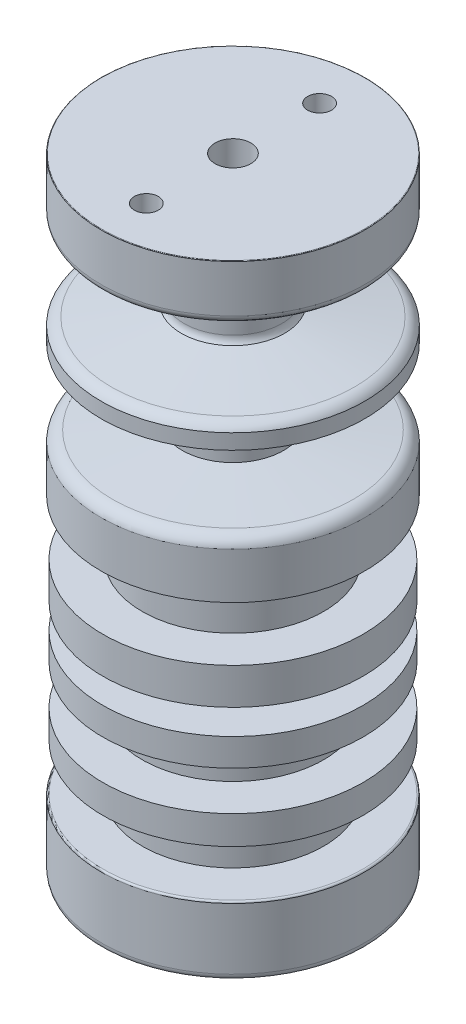
SolidWorks part; units mm, degrees
ref_plane "Alzado" through (0, 0, 0) normal (0, 0, 1) x (1, 0, 0)
ref_plane "Planta" through (0, 0, 0) normal (0, 1, 0) x (1, 0, 0)
ref_plane "Vista lateral" through (0, 0, 0) normal (1, 0, 0) x (0, 0, -1)
sketch "Croquis1" plane through (0, 0, 0) normal (0, 0, 1) x (1, 0, 0)
  line L0 (0, 0) -> (0, 43.0446) construction
  line L1 (0, 43.0446) -> (0, -121.9554) construction
  line L2 (0, 43.0446) -> (34.8584, 43.0446)
  line L3 (35, 42.903) -> (35, 30.366)
  line L4 (32.9644, 28.3304) -> (12.9858, 28.3304)
  line L5 (12.9858, 28.3304) -> (12.9858, 10.4062)
  line L6 (13.718, 8.5125) -> (32.3097, 5.486)
  line L7 (35, 3.5416) -> (35, -0.4901)
  line L8 (13.4687, -0.4901) -> (35, -0.4901)
  line L9 (13.4687, -0.4901) -> (13.4687, -18.5388)
  line L10 (13.4687, -18.5388) -> (31.9792, -20.5132)
  line L11 (35, -23.2242) -> (35, -35.5011)
  line L12 (24.0861, -91.9234) -> (34.5383, -91.9234)
  line L13 (24.0861, -91.9234) -> (24.0861, -104.2217)
  line L14 (24.0861, -104.2217) -> (34.5383, -104.2217)
  line L15 (35, -104.6833) -> (35, -120.9509)
  line L16 (34.7378, -121.991) -> (0, -121.9554)
  line L17 (0, 43.0446) -> (0, -121.9554)
  line L18 (34.5383, -91.9234) -> (34.5383, -84.3501)
  line L19 (35, -35.5011) -> (24.0861, -35.5011)
  line L20 (24.0861, -35.5011) -> (24.0861, -50.2633)
  line L21 (34.5383, -84.3501) -> (24.0861, -84.3501)
  line L22 (24.0861, -73.9073) -> (34.5383, -73.9073)
  line L23 (34.5383, -73.9073) -> (34.5383, -66.6171)
  line L24 (34.5383, -66.6171) -> (24.0861, -66.6171)
  line L25 (24.0861, -59.9179) -> (34.5383, -59.9179)
  line L26 (34.5383, -59.9179) -> (34.5383, -50.2633)
  line L27 (34.5383, -50.2633) -> (24.0861, -50.2633)
  line L28 (24.0861, -73.9073) -> (24.0861, -84.3501)
  line L29 (24.0861, -59.9179) -> (24.0861, -66.6171)
  arc A0 (34.8584, 43.0446) -> (35, 42.903) centre (34.8584, 42.903) cw
  arc A1 (35, 30.366) -> (32.9644, 28.3304) centre (32.9644, 30.366) cw
  arc A2 (12.9858, 10.4062) -> (13.718, 8.5125) centre (15.8008, 10.4062) ccw
  arc A3 (32.3097, 5.486) -> (35, 3.5416) centre (31.7144, 1.829) cw
  arc A6 (31.9792, -20.5132) -> (35, -23.2242) centre (31.6114, -23.9615) cw
  arc A8 (34.5383, -104.2217) -> (35, -104.6833) centre (34.5383, -104.6833) cw
  arc A9 (35, -120.9509) -> (34.7378, -121.991) centre (32.8058, -120.9509) cw
  dimension "D1" = 165
  dimension "D2" = 34.8584
  dimension "D3" = 35
  dimension "D4" = 35
  dimension "D5" = 35
revolve "Revolución3" add sketch "Croquis1" angle 360 about L17
sketch "Croquis2" plane through (0, 43.0446, 0) normal (0, 1, 0) x (1, 0, 0)
  line L1 (-0.2111, -19.8252) -> (0, 0) construction
  line L2 (0, 0) -> (11.2888, 0) construction
  line L4 (34.8584, 0) -> (-34.8584, 0) construction
  line L5 (-34.8584, 0) -> (0, 0) construction
  line L6 (0, 0) -> (0, 34.8584) construction
  line L7 (0, 34.8584) -> (0, -34.8584) construction
  circle A0 centre (0, 23) radius 3.175
  circle A1 centre (0, 0) radius 34.8584 construction
  circle A2 centre (0, -23) radius 3.175
  point P4 (0, 0)
  point P7 (0, 0)
  dimension "D3" = 6.35
  dimension "D4" = 6.35
  dimension "D1" = 23
  dimension "D2" = 23
extrude "Cortar-Extruir2" cut sketch "Croquis2" against normal blind 12
sketch "Croquis6" plane through (0, 43.0446, 0) normal (0, 1, 0) x (1, 0, 0)
  circle A0 centre (0, 0) radius 4.7625
  dimension "D1" = 9.525
extrude "Cortar-Extruir4" cut sketch "Croquis6" against normal blind 12
ref_plane "Plano1" through (0, 0, 0) normal (1, 0, 0) x (0, 0, -1)
ref_plane "Plano2" through (0, 0, 0) normal (0, 0, 1) x (1, 0, 0)
ref_plane "Plano3" through (0, -126.9554, 0) normal (0, 1, 0) x (1, 0, 0)
sketch "Croquis11" plane through (0, -126.9554, 0) normal (0, 1, 0) x (1, 0, 0)
  circle A0 centre (0, 0) radius 7.9375
  dimension "D1" = 15.875
extrude "Cortar-Extruir7" cut sketch "Croquis11" along normal blind 53
